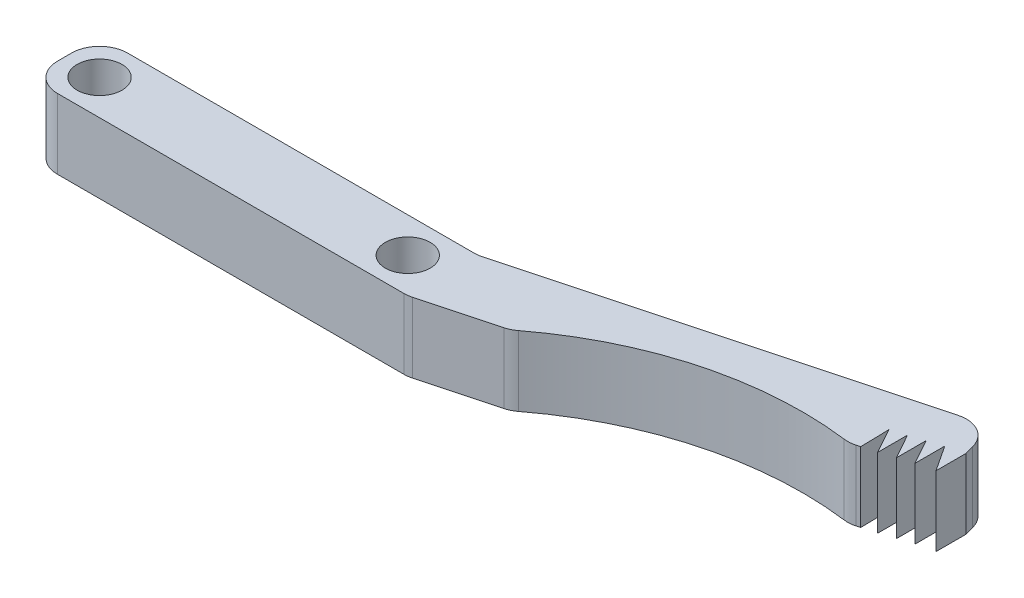
SolidWorks part; units mm, degrees
ref_plane "前视基准面" through (0, 0, 0) normal (0, 0, 1) x (1, 0, 0)
ref_plane "上视基准面" through (0, 0, 0) normal (0, 1, 0) x (1, 0, 0)
ref_plane "右视基准面" through (0, 0, 0) normal (1, 0, 0) x (0, 0, -1)
sketch "草图1" plane through (0, 0, 0) normal (0, 1, 0) x (1, 0, 0)
  line L0 (0, -55) -> (0, 55) construction
  line L1 (-13.5, 2.5) -> (13.5, 2.5)
  line L2 (-13.5, 2.5) -> (-13.5, -2.5)
  line L3 (-13.5, -2.5) -> (13.5, -2.5)
  line L5 (-13.5, 2.5) -> (13.5, -2.5) construction
  line L6 (-13.5, -2.5) -> (13.5, 2.5) construction
  line L7 (13.5, 2.5) -> (42.4778, 10.2646)
  line L8 (42.4778, 10.2646) -> (43.1762, 7.6581)
  line L9 (39.0009, 4.333) -> (38.3341, 4.1543)
  line L10 (19.2956, -0.9471) -> (13.5, -2.5)
  line L13 (39.0009, 4.333) -> (38.9534, 6.3908)
  line L14 (38.9534, 6.3908) -> (39.957, 4.5891)
  line L15 (39.957, 4.5891) -> (39.957, 6.7175)
  line L16 (39.957, 6.7175) -> (40.9607, 4.9159)
  line L17 (40.9607, 4.9159) -> (40.9607, 7.0442)
  line L18 (40.9607, 7.0442) -> (41.9644, 5.2426)
  line L19 (41.9644, 5.2426) -> (41.9644, 7.371)
  line L20 (41.9644, 7.371) -> (43.1762, 5.5297)
  line L21 (43.1762, 5.5297) -> (43.1762, 7.6581)
  circle A0 centre (-11, 0) radius 1.6
  circle A1 centre (11, 0) radius 1.6
  arc A2 (19.2956, -0.9471) -> (38.3341, 4.1543) centre (34.7613, -20.5891) cw
  point P0 (0, 0)
  dimension "D2" = 3.2
  dimension "D9" = 25
  dimension "D1" = 5
  dimension "D3" = 11
  dimension "D4" = 2.5
  dimension "D5" = 165
  dimension "D6" = 30
  dimension "D7" = 6
extrude "凸台-拉伸1" add sketch "草图1" along normal blind 5
fillet "圆角1" radius 2 7 edges at (13.5, 2.5, -2.5) (42.4778, 2.5, -10.2646) (38.3341, 2.5, -4.1543) (19.2956, 2.5, 0.9471) (13.5, 2.5, 2.5) (-13.5, 2.5, -2.5) (-13.5, 2.5, 2.5)
